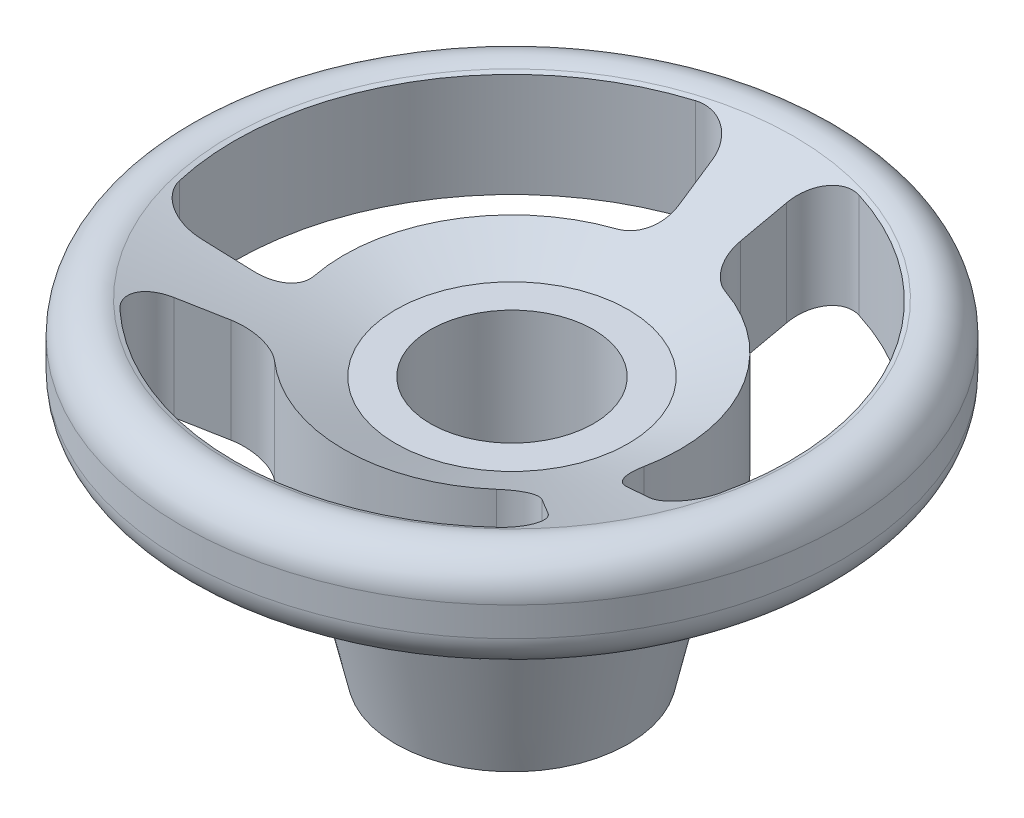
SolidWorks part; units mm, degrees
ref_plane "Plan de face" through (0, 0, 0) normal (0, 0, 1) x (1, 0, 0)
ref_plane "Plan de dessus" through (0, 0, 0) normal (0, 1, 0) x (1, 0, 0)
ref_plane "Plan de droite" through (0, 0, 0) normal (1, 0, 0) x (0, 0, -1)
sketch "Esquisse2" plane through (0, 0, 0) normal (0, 0, 1) x (1, 0, 0)
  line L0 (0, 0) -> (0, 42.0643) construction
  line L1 (4.7, 0) -> (4.7, 20)
  line L2 (4.7, 20) -> (6.7, 20)
  line L3 (6.7, 20) -> (6.7, 15)
  line L4 (6.7, 15) -> (19, 20)
  line L5 (19, 20) -> (19, 14)
  line L6 (19, 14) -> (9, 9.935)
  line L7 (9, 9.935) -> (6.7, 0)
  line L8 (6.7, 0) -> (4.7, 0)
  line L9 (4.7, 0) -> (0, 0) construction
  line L10 (19, 20) -> (6.7, 20) construction
  dimension "D1" = 9.4
  dimension "D2" = 2
  dimension "D3" = 18
  dimension "D4" = 2
  dimension "D5" = 38
  dimension "D6" = 6
  dimension "D7" = 20
  dimension "D8" = 5
revolve "Révolution1" add sketch "Esquisse2" angle 360 about L0
sketch "Esquisse3" plane through (0, 20, 0) normal (0, 1, 0) x (1, 0, 0)
  line L0 (0, 0) -> (0, 19) construction
  line L1 (0, 0) -> (-1.5, 9.5833) construction
  line L2 (-1.5, 9.5833) -> (-2.4742, 15.8075)
  line L3 (-9.0494, -3.4926) -> (-14.9268, -5.761)
  line L4 (-9.0494, -3.4926) -> (0, 0) construction
  line L5 (0, 0) -> (-16.4545, -9.5) construction
  line L6 (9.0494, -3.4926) -> (14.9268, -5.761)
  line L7 (1.5, 9.5833) -> (2.4742, 15.8075)
  line L8 (-7.5494, -6.0907) -> (-12.4526, -10.0465)
  line L9 (7.5494, -6.0907) -> (12.4526, -10.0465)
  circle A0 centre (0, 0) radius 19 construction
  arc A1 (-1.5, 9.5833) -> (-9.0494, -3.4926) centre (0, 0) ccw
  arc A2 (-2.4742, 15.8075) -> (-14.9268, -5.761) centre (0, 0) ccw
  circle A3 centre (0, 0) radius 6.7 construction
  arc A4 (9.0494, -3.4926) -> (1.5, 9.5833) centre (0, 0) ccw
  arc A5 (14.9268, -5.761) -> (2.4742, 15.8075) centre (0, 0) ccw
  arc A6 (-7.5494, -6.0907) -> (7.5494, -6.0907) centre (0, 0) ccw
  arc A7 (-12.4526, -10.0465) -> (12.4526, -10.0465) centre (0, 0) ccw
  point P23 (0, 0)
  dimension "D1" = 3
  dimension "D2" = 3
  dimension "D3" = 3
  dimension "D4" = 120
  dimension "D5" = 3
  dimension "D6" = 3
extrude "Enlèv. mat.-Extru.1" cut sketch "Esquisse3" against normal through all both and the other way through all
fillet "Congé1" radius 2 2 edges at (0, 14, -19) (0, 20, -19)
fillet "Congé2" radius 2 12 edges at (-14.9268, 15.7805, 5.761) (-2.4742, 15.7805, -15.8075) (2.4742, 15.7805, -15.8075) (14.9268, 15.7805, 5.761) (12.4526, 15.7805, 10.0465) (7.5494, 13.2195, 6.0907) (-7.5494, 13.2195, 6.0907) (-12.4526, 15.7805, 10.0465) (9.0494, 13.2195, 3.4926) (1.5, 13.2195, -9.5833) (-1.5, 13.2195, -9.5833) (-9.0494, 13.2195, 3.4926)
sketch "Esquisse4" plane through (0, 20, 0) normal (0, 1, 0) x (1, 0, 0)
  circle A0 centre (0, 0) radius 6.7
  circle A1 centre (0, 0) radius 6.7 construction
extrude "Enlèv. mat.-Extru.2" cut sketch "Esquisse4" against normal blind 5
